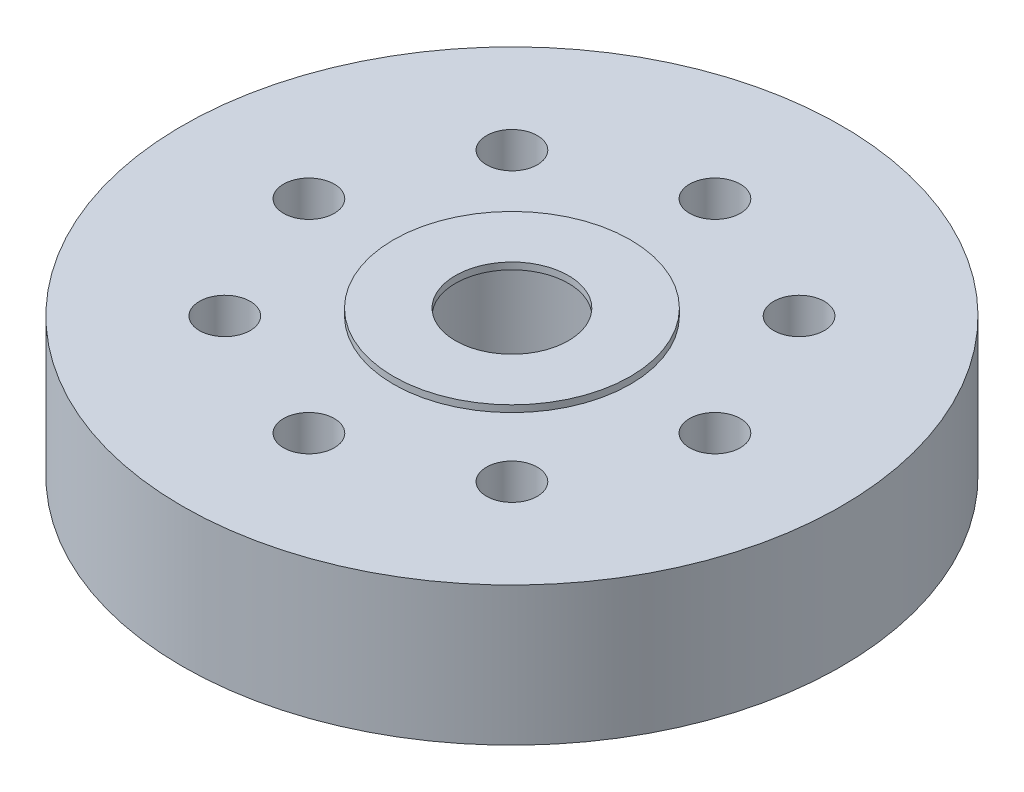
SolidWorks part; units mm, degrees
ref_plane "Front Plane" through (0, 0, 0) normal (0, 0, 1) x (1, 0, 0)
ref_plane "Top Plane" through (0, 0, 0) normal (0, 1, 0) x (1, 0, 0)
ref_plane "Right Plane" through (0, 0, 0) normal (1, 0, 0) x (0, 0, -1)
sketch "Sketch1" plane through (0, 0, 0) normal (0, 1, 0) x (1, 0, 0)
  circle A0 centre (0, 0) radius 9.74
  circle A2 centre (0, 0) radius 2.57
  dimension "D1" = 5.14
  dimension "D2" = 19.48
extrude "MountBody" add sketch "Sketch1" along normal blind 4.1
sketch "Sketch2" plane through (0, 4.1, 0) normal (0, 1, 0) x (1, 0, 0)
  circle A0 centre (0, 0) radius 3.5
  circle A1 centre (0, 0) radius 1.67
  dimension "D1" = 3.34
  dimension "D2" = 7
extrude "Cap" add sketch "Sketch2" along normal blind 0.2
sketch "Sketch3" plane through (0, 4.1, 0) normal (0, 1, 0) x (1, 0, 0)
  circle A0 centre (6, 0) radius 0.75
  circle A3 centre (4.2426, -4.2426) radius 0.75
  circle A4 centre (0, -6) radius 0.75
  circle A5 centre (-4.2426, -4.2426) radius 0.75
  circle A6 centre (-6, 0) radius 0.75
  circle A7 centre (-4.2426, 4.2426) radius 0.75
  circle A8 centre (0, 6) radius 0.75
  circle A9 centre (4.2426, 4.2426) radius 0.75
  point P19 (0, 0)
  dimension "D1" = 1.5
  dimension "D2" = 8
  dimension "D3" = 6
extrude "ScrewHoles" cut sketch "Sketch3" against normal through all
